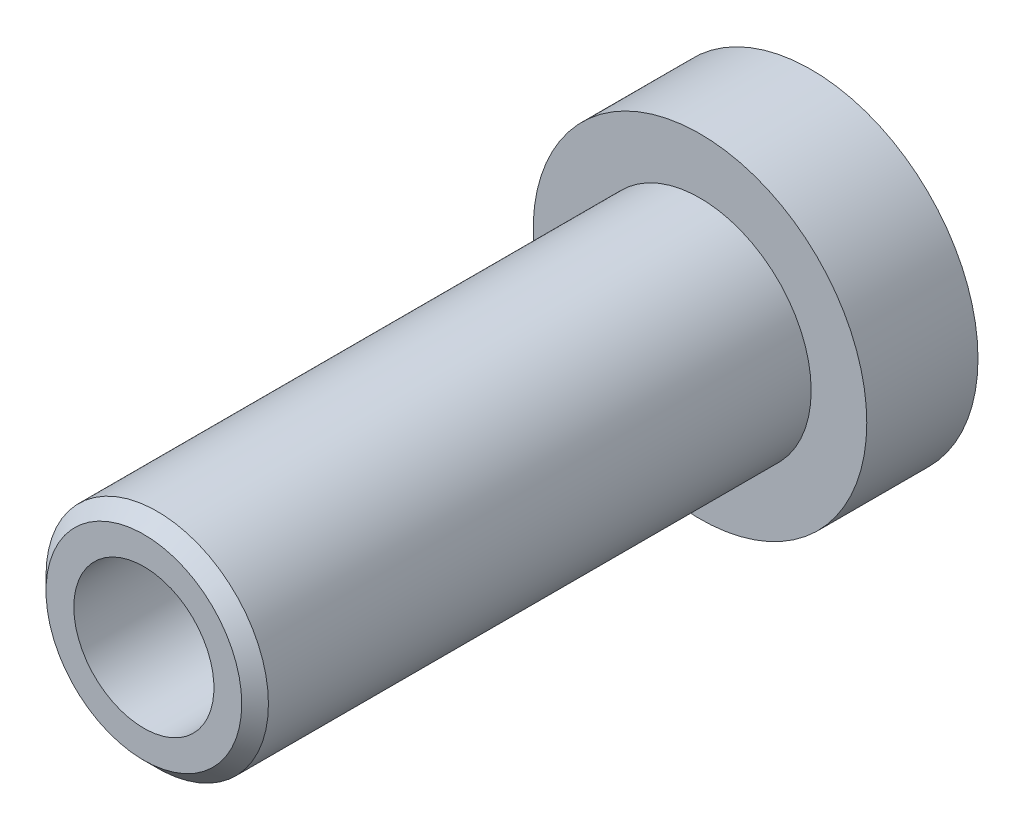
SolidWorks part; units mm, degrees
ref_plane "Front Plane" through (0, 0, 0) normal (0, 0, 1) x (1, 0, 0)
ref_plane "Top Plane" through (0, 0, 0) normal (0, 1, 0) x (1, 0, 0)
ref_plane "Right Plane" through (0, 0, 0) normal (1, 0, 0) x (0, 0, -1)
sketch "Sketch1" plane through (0, 0, 0) normal (0, 0, 1) x (1, 0, 0)
  line L0 (-2.2516, 0) -> (2.1666, 0) construction
  line L1 (0.0014, 1.5719) -> (0.0014, -1.763) construction
  circle A0 centre (0, 0) radius 0.75
  dimension "D1" = 1.5
extrude "Boss-Extrude1" add sketch "Sketch1" along normal blind 0.5
sketch "Sketch2" plane through (0, 0, 0.5) normal (0, 0, 1) x (1, 0, 0)
  circle A0 centre (0, 0) radius 0.5
  dimension "D1" = 1
extrude "Boss-Extrude2" add sketch "Sketch2" along normal blind 2.5
sketch "Sketch3" plane through (0, 0, 0) normal (0, 0, -1) x (-1, 0, 0)
  circle A0 centre (0, 0) radius 0.315
  dimension "D1" = 0.63
extrude "Cut-Extrude1" cut sketch "Sketch3" against normal blind 3
chamfer "Chamfer1" distance 0.06 angle 45 1 edges at (0.5, 0, 3)
